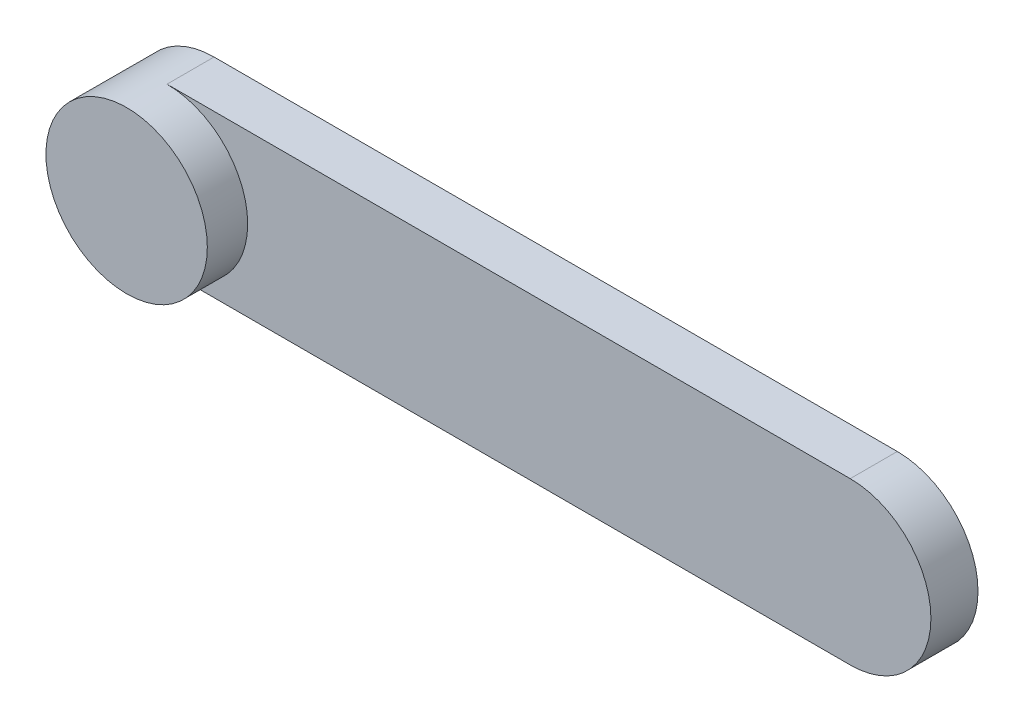
SolidWorks part; units mm, degrees
ref_plane "前视基准面" through (0, 0, 0) normal (0, 0, 1) x (1, 0, 0)
ref_plane "上视基准面" through (0, 0, 0) normal (0, 1, 0) x (1, 0, 0)
ref_plane "右视基准面" through (0, 0, 0) normal (1, 0, 0) x (0, 0, -1)
other "Configuration Table"
sketch "草图1" plane through (0, 0, 0) normal (0, 0, 1) x (1, 0, 0)
  line L0 (0, 6) -> (50.8, 6)
  line L1 (50.8, -6) -> (0, -6)
  arc A0 (0, 6) -> (0, -6) centre (0, 0) ccw
  arc A1 (50.8, -6) -> (50.8, 6) centre (50.8, 0) ccw
  dimension "D1" = 6
  dimension "D2" = 6
  dimension "D3" = 50.8
extrude "凸台-拉伸1" add sketch "草图1" along normal mid plane 3.5
sketch "草图2" plane through (0, 0, 1.75) normal (0, 0, 1) x (1, 0, 0)
  circle A0 centre (0, 0) radius 6
extrude "凸台-拉伸2" add sketch "草图2" along normal blind 3
